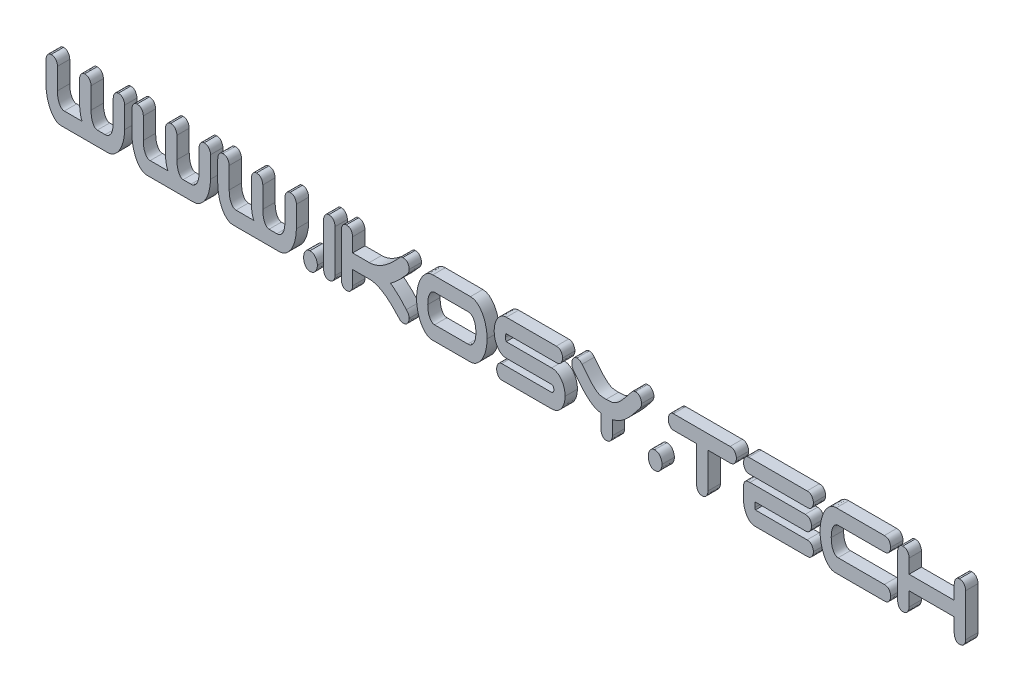
SolidWorks part; units mm, degrees
other "Text Extrude - I"
other "Text Extrude - ."
other "Text Extrude - W3"
other "Text Extrude - W2"
other "Text Extrude - W1" parameters "D1"=19.4587, "D2"=1.1925, "Border Width"=2.5
ref_plane "Front Plane" through (0, 0, 0) normal (0, 0, 1) x (1, 0, 0)
ref_plane "Top Plane" through (0, 0, 0) normal (0, 1, 0) x (1, 0, 0)
ref_plane "Right Plane" through (0, 0, 0) normal (1, 0, 0) x (0, 0, -1)
sketch "Insertion Point Sketch" plane through (0, 0, 0) normal (0, 0, 1) x (1, 0, 0)
  line L0 (-3.25, -3.25) -> (-3.25, 0) construction
  line L1 (-3.25, -3.25) -> (0, -3.25) construction
  dimension "D1" = 3.25
  dimension "D2" = 3.25
sketch "Text Sketch" plane through (0, 0, 0) normal (0, 0, 1) x (1, 0, 0)
  line L0 (-3.25, 16.75) -> (187.5, 16.75) construction
  line L1 (187.5, 16.75) -> (187.5, -3.25) construction
  line L2 (187.5, -3.25) -> (-3.25, -3.25) construction
  line L3 (187.5, 14.25) -> (-0.75, 14.25) construction
  line L4 (187.5, -0.75) -> (-0.75, -0.75) construction
  line L5 (-3.25, 16.75) -> (-3.25, -3.25) construction
  line L6 (-0.75, -0.75) -> (-0.75, 14.25) construction
  text T0 "www.ikosy.tech" font "Space Age" height 11.5
  dimension "D2" = 20
  dimension "D4" = 187.5
extrude "Text Extrude" add sketch "Text Sketch" along normal blind 2.5 separate body
equation "\"Logo Height\"= \"Total Height\" - 2 * \"Border\""
equation "\"Total Height\"= 40mm"
equation "\"Border\"= 3.25mm"
equation "\"Symbol Width\"= \"Logo Height\" * 0.75"
equation "\"Line Width\"= \"Symbol Width\" / 15"
equation "\"Ikosy X Position\"= \"Symbol Width\" + 5mm"
equation "\"Ikosy Y Position\"= ( 1 - 0.55 ) * \"Logo Height\" - 3"
equation "\"D1@Insertion Point Sketch\" = \"Border\""
equation "\"D2@Insertion Point Sketch\" = \"Border\""
